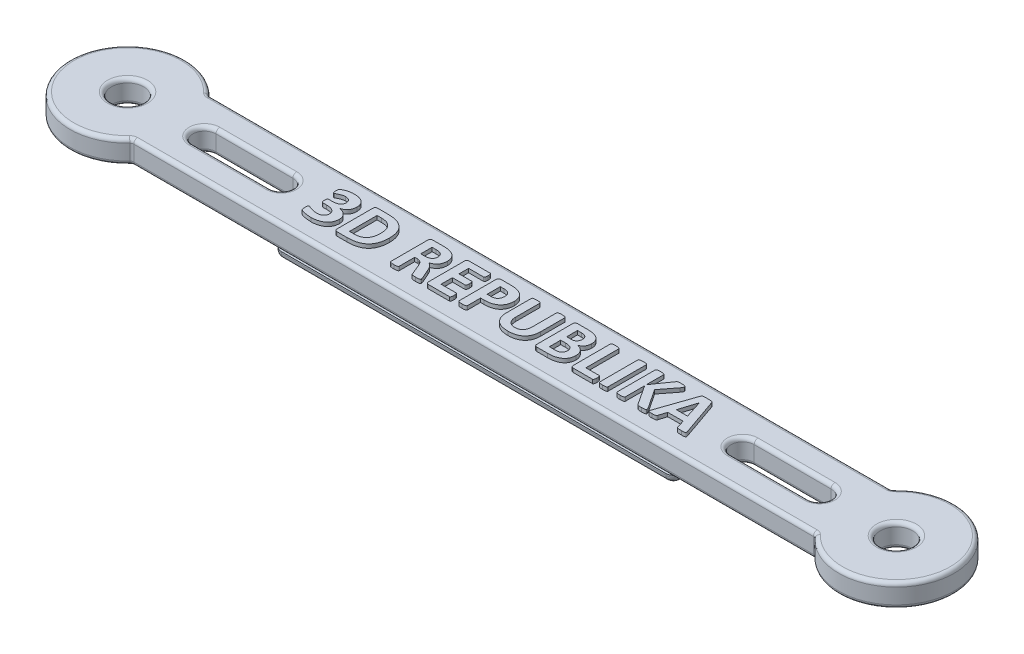
SolidWorks part; units mm, degrees
ref_plane "Front Plane" through (0, 0, 0) normal (0, 0, 1) x (1, 0, 0)
ref_plane "Top Plane" through (0, 0, 0) normal (0, 1, 0) x (1, 0, 0)
ref_plane "Right Plane" through (0, 0, 0) normal (1, 0, 0) x (0, 0, -1)
sketch "Sketch1" plane through (0, 0, 0) normal (0, 1, 0) x (1, 0, 0)
  line L0 (5.5902, 5) -> (94.4098, 5)
  line L1 (5.5902, -5) -> (94.4098, -5)
  arc A0 (5.5902, 5) -> (5.5902, -5) centre (0, 0) ccw
  circle A1 centre (0, 0) radius 2.1
  arc A2 (94.4098, -5) -> (94.4098, 5) centre (100, 0) ccw
  circle A3 centre (100, 0) radius 2.1
  dimension "D1" = 15
  dimension "D2" = 4.2
  dimension "D3" = 15
  dimension "D4" = 4.2
  dimension "D5" = 100
  dimension "D6" = 5
  dimension "D7" = 10
extrude "Boss-Extrude1" add sketch "Sketch1" along normal blind 3
sketch "Sketch2" plane through (0, 3, 0) normal (0, 1, 0) x (1, 0, 0)
  line L0 (-7.0166, -2.6491) -> (107.0166, -2.6491) construction
  arc A0 (94.4098, -5) -> (94.4098, 5) centre (100, 0) ccw construction
  arc A1 (5.5902, 5) -> (5.5902, -5) centre (0, 0) ccw construction
  text T0 "3D REPUBLIKA" font "Calibri" height in points 20
extrude "Boss-Extrude2" add sketch "Sketch2" along normal blind 0.5
sketch "Sketch3" plane through (0, 3, 0) normal (0, 1, 0) x (1, 0, 0)
  line L0 (50, 5) -> (50, 12.6225) construction
  line L1 (94.4098, 5) -> (5.5902, 5) construction
  line L2 (10, 0) -> (20, 0) construction
  line L3 (10, 1.5) -> (20, 1.5)
  line L4 (10, -1.5) -> (20, -1.5)
  line L5 (90, 0) -> (80, 0) construction
  line L6 (90, 1.5) -> (80, 1.5)
  line L7 (90, -1.5) -> (80, -1.5)
  arc A0 (10, 1.5) -> (10, -1.5) centre (10, 0) ccw
  arc A1 (20, -1.5) -> (20, 1.5) centre (20, 0) ccw
  arc A2 (90, 1.5) -> (90, -1.5) centre (90, 0) cw
  arc A3 (80, -1.5) -> (80, 1.5) centre (80, 0) cw
  point P8 (15, 0)
  point P16 (85, 0)
  dimension "D1" = 10
  dimension "D2" = 10
  dimension "D3" = 1.5
extrude "Cut-Extrude1" cut sketch "Sketch3" against normal blind 6
sketch "Sketch4" plane through (0, 0, 0) normal (0, -1, 0) x (1, 0, 0)
  line L0 (5.5902, 5) -> (94.4098, 5) construction
  line L1 (24, 5) -> (76, 5)
  line L2 (24, 5) -> (24, -5)
  line L3 (24, -5) -> (76, -5)
  line L4 (76, 5) -> (76, -5)
  line L5 (94.4098, -5) -> (5.5902, -5) construction
  dimension "D1" = 52
  dimension "D2" = 24
extrude "Boss-Extrude3" add sketch "Sketch4" along normal blind 1 separate body
fillet "Fillet1" radius 1 4 edges at (76, -0.5, 5) (76, -0.5, -5) (24, -0.5, -5) (24, -0.5, 5)
fillet "Fillet2" radius 0.8 8 edges at (50, -1, -5) (24.2929, -1, -4.7071) (24, -1, 0) (24.2929, -1, 4.7071) (50, -1, 5) (75.7071, -1, 4.7071) (76, -1, 0) (75.7071, -1, -4.7071)
fillet "Fillet3" radius 0.5 32 edges at (50, 3, -5) (50, 0, -5) (21.5, 0, 0) (15, 0, 1.5) (8.5, 0, 0) (21.5, 3, 0) (15, 3, 1.5) (8.5, 3, 0) (91.5, 0, 0) (85, 0, 1.5) (78.5, 0, 0) (91.5, 3, 0) (85, 3, 1.5) (78.5, 3, 0) (0, 0, 2.1) (0, 3, 2.1) (15, 0, -1.5) (15, 3, -1.5) (85, 0, -1.5) (85, 3, -1.5) (100, 0, 2.1) (100, 3, 2.1) (107.5, 3, 0) (94.4098, 1.5, -5) (107.5, 0, 0) (5.5902, 1.5, -5) (-7.5, 3, 0) (-7.5, 0, 0) (5.5902, 1.5, 5) (50, 3, 5) (94.4098, 1.5, 5) (50, 0, 5)
